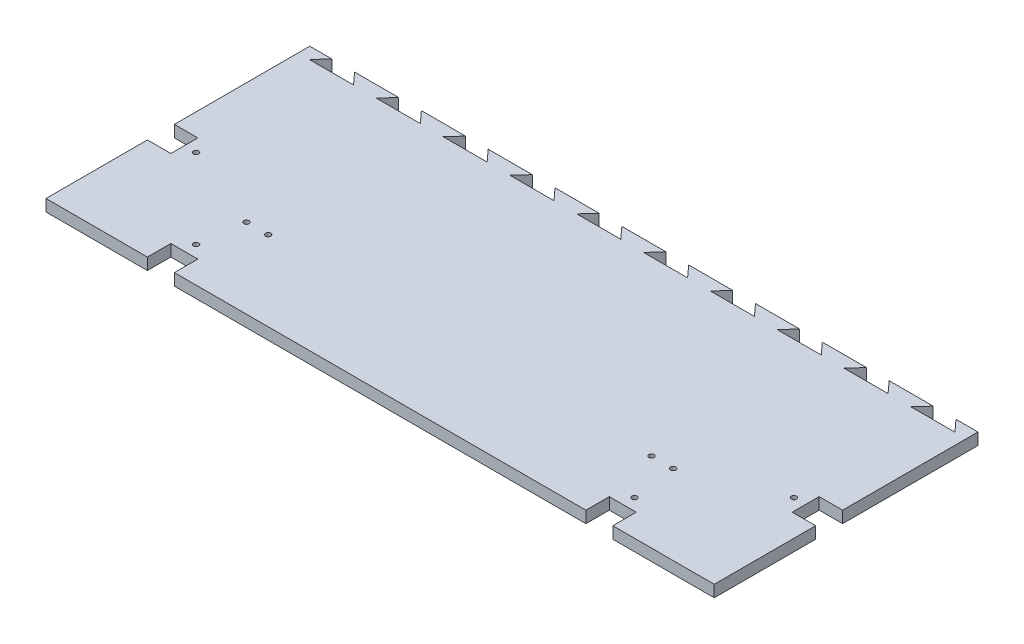
SolidWorks part; units mm, degrees
material "Multistrato di pioppo"
ref_plane "Piano frontale" through (0, 0, 0) normal (0, 0, 1) x (1, 0, 0)
ref_plane "Piano superiore" through (0, 0, 0) normal (0, 1, 0) x (1, 0, 0)
ref_plane "Piano destro" through (0, 0, 0) normal (1, 0, 0) x (0, 0, -1)
sketch "Schizzo1" plane through (0, 0, 0) normal (0, 1, 0) x (1, 0, 0)
  line L1 (0, 0) -> (-570, 0)
  line L2 (0, 0) -> (0, 450)
  line L3 (0, 450) -> (-570, 450)
  line L4 (-570, 0) -> (-570, 450)
  dimension "D1" = 570
  dimension "D2" = 450
extrude "Estrusione-Estrusione1" add sketch "Schizzo1" along normal blind 10
sketch "Schizzo2" plane through (0, 0, 0) normal (0, -1, 0) x (1, 0, 0)
  line L0 (-570, 0) -> (0, 0) construction
  line L1 (-483.5, 0) -> (-460.5, 0)
  line L3 (-483.5, 0) -> (-483.5, -20)
  line L5 (-483.5, -20) -> (-460.5, -20)
  line L6 (-460.5, 0) -> (-460.5, -20)
  line L7 (-483.5, 0) -> (-460.5, -20) construction
  line L8 (-483.5, -20) -> (-460.5, 0) construction
  line L9 (0, 0) -> (0, -450) construction
  line L10 (-109.5, 0) -> (-86.5, 0)
  line L11 (-109.5, 0) -> (-109.5, -20)
  line L12 (-109.5, -20) -> (-86.5, -20)
  line L13 (-86.5, 0) -> (-86.5, -20)
  line L14 (-109.5, 0) -> (-86.5, -20) construction
  line L15 (-109.5, -20) -> (-86.5, 0) construction
  line L16 (0, -86.5) -> (-20, -86.5)
  line L17 (0, -86.5) -> (0, -109.5)
  line L18 (0, -109.5) -> (-20, -109.5)
  line L19 (-20, -86.5) -> (-20, -109.5)
  line L20 (0, -86.5) -> (-20, -109.5) construction
  line L21 (0, -109.5) -> (-20, -86.5) construction
  line L22 (0, -450) -> (-570, -450) construction
  line L23 (0, -340.5) -> (-20, -340.5)
  line L24 (0, -340.5) -> (0, -363.5)
  line L25 (0, -363.5) -> (-20, -363.5)
  line L26 (-20, -340.5) -> (-20, -363.5)
  line L27 (0, -340.5) -> (-20, -363.5) construction
  line L28 (0, -363.5) -> (-20, -340.5) construction
  line L29 (-86.5, -450) -> (-109.5, -450)
  line L30 (-86.5, -450) -> (-86.5, -430)
  line L31 (-86.5, -430) -> (-109.5, -430)
  line L32 (-109.5, -450) -> (-109.5, -430)
  line L33 (-86.5, -450) -> (-109.5, -430) construction
  line L34 (-86.5, -430) -> (-109.5, -450) construction
  line L35 (-570, -450) -> (-570, 0) construction
  line L36 (-460.5, -450) -> (-483.5, -450)
  line L37 (-460.5, -450) -> (-460.5, -430)
  line L38 (-460.5, -430) -> (-483.5, -430)
  line L39 (-483.5, -450) -> (-483.5, -430)
  line L40 (-460.5, -450) -> (-483.5, -430) construction
  line L41 (-460.5, -430) -> (-483.5, -450) construction
  line L42 (-570, -363.5) -> (-550, -363.5)
  line L43 (-570, -363.5) -> (-570, -340.5)
  line L44 (-570, -340.5) -> (-550, -340.5)
  line L45 (-550, -363.5) -> (-550, -340.5)
  line L46 (-570, -363.5) -> (-550, -340.5) construction
  line L47 (-570, -340.5) -> (-550, -363.5) construction
  line L48 (-560, -98) -> (-10, -98) construction
  line L49 (-570, -109.5) -> (-550, -109.5)
  line L50 (-570, -109.5) -> (-570, -86.5)
  line L51 (-570, -86.5) -> (-550, -86.5)
  line L52 (-550, -109.5) -> (-550, -86.5)
  line L53 (-570, -109.5) -> (-550, -86.5) construction
  line L54 (-570, -86.5) -> (-550, -109.5) construction
  line L55 (-472, -10) -> (-472, -440) construction
  line L56 (-98, -440) -> (-98, -10) construction
  line L57 (-560, -352) -> (-10, -352) construction
  circle A2 centre (-467, -68) radius 2.25
  circle A3 centre (-448.5, -68) radius 2.25
  circle A6 centre (-121.5, -68) radius 2.25
  circle A7 centre (-103, -68) radius 2.25
  circle A8 centre (-467, -382) radius 2.25
  circle A9 centre (-448.5, -382) radius 2.25
  circle A14 centre (-121.5, -382) radius 2.25
  circle A15 centre (-103, -382) radius 2.25
  circle A16 centre (-472, -420) radius 2.25
  circle A17 centre (-540, -352) radius 2.25
  circle A18 centre (-540, -98) radius 2.25
  circle A19 centre (-472, -30) radius 2.25
  circle A20 centre (-98, -30) radius 2.25
  circle A21 centre (-30, -98) radius 2.25
  circle A22 centre (-30, -352) radius 2.25
  circle A23 centre (-98, -420) radius 2.25
  point P4 (-472, -10)
  point P17 (-98, -10)
  point P34 (-10, -98)
  point P41 (-10, -352)
  point P52 (-98, -440)
  point P59 (-472, -440)
  point P64 (-560, -352)
  point P71 (-560, -98)
  dimension "D1" = 4.5
  dimension "D3" = 98
  dimension "D5" = 98
  dimension "D2" = 98
  dimension "D4" = 98
  dimension "D6" = 23
  dimension "D7" = 20
extrude "Taglio-Estrusione1" cut sketch "Schizzo2" against normal blind 10
sketch "Schizzo3" plane through (0, 0, 0) normal (0, -1, 0) x (1, 0, 0)
  line L0 (-570, -225) -> (-551.2, -225)
  line L1 (-570, -340.5) -> (-570, -109.5) construction
  line L2 (-551.2, -225) -> (-560.3, -215)
  line L3 (-560.3, -215) -> (-522.7, -215)
  line L4 (-522.7, -215) -> (-531.8, -225)
  line L5 (-531.8, -225) -> (-513, -225)
  line L6 (-551.2, -225) -> (-531.8, -225) construction
  line L7 (-541.5, -225) -> (-541.5, -215) construction
  line L8 (-513, -225) -> (-494.2, -225)
  line L9 (-494.2, -225) -> (-503.3, -215)
  line L10 (-503.3, -215) -> (-465.7, -215)
  line L11 (-465.7, -215) -> (-474.8, -225)
  line L12 (-474.8, -225) -> (-456, -225)
  line L13 (-494.2, -225) -> (-474.8, -225) construction
  line L14 (-484.5, -225) -> (-484.5, -215) construction
  line L15 (-456, -225) -> (-437.2, -225)
  line L16 (-437.2, -225) -> (-446.3, -215)
  line L17 (-446.3, -215) -> (-408.7, -215)
  line L18 (-408.7, -215) -> (-417.8, -225)
  line L19 (-417.8, -225) -> (-399, -225)
  line L20 (-437.2, -225) -> (-417.8, -225) construction
  line L21 (-427.5, -225) -> (-427.5, -215) construction
  line L22 (-399, -225) -> (-380.2, -225)
  line L23 (-380.2, -225) -> (-389.3, -215)
  line L24 (-389.3, -215) -> (-351.7, -215)
  line L25 (-351.7, -215) -> (-360.8, -225)
  line L26 (-360.8, -225) -> (-342, -225)
  line L27 (-380.2, -225) -> (-360.8, -225) construction
  line L28 (-370.5, -225) -> (-370.5, -215) construction
  line L29 (-342, -225) -> (-323.2, -225)
  line L30 (-323.2, -225) -> (-332.3, -215)
  line L31 (-332.3, -215) -> (-294.7, -215)
  line L32 (-294.7, -215) -> (-303.8, -225)
  line L33 (-303.8, -225) -> (-285, -225)
  line L34 (-323.2, -225) -> (-303.8, -225) construction
  line L35 (-313.5, -225) -> (-313.5, -215) construction
  line L36 (-285, -225) -> (-266.2, -225)
  line L37 (-266.2, -225) -> (-275.3, -215)
  line L38 (-275.3, -215) -> (-237.7, -215)
  line L39 (-237.7, -215) -> (-246.8, -225)
  line L40 (-246.8, -225) -> (-228, -225)
  line L41 (-266.2, -225) -> (-246.8, -225) construction
  line L42 (-256.5, -225) -> (-256.5, -215) construction
  line L43 (-228, -225) -> (-209.2, -225)
  line L44 (-209.2, -225) -> (-218.3, -215)
  line L45 (-218.3, -215) -> (-180.7, -215)
  line L46 (-180.7, -215) -> (-189.8, -225)
  line L47 (-189.8, -225) -> (-171, -225)
  line L48 (-209.2, -225) -> (-189.8, -225) construction
  line L49 (-199.5, -225) -> (-199.5, -215) construction
  line L50 (-171, -225) -> (-152.2, -225)
  line L51 (-152.2, -225) -> (-161.3, -215)
  line L52 (-161.3, -215) -> (-123.7, -215)
  line L53 (-123.7, -215) -> (-132.8, -225)
  line L54 (-132.8, -225) -> (-114, -225)
  line L55 (-152.2, -225) -> (-132.8, -225) construction
  line L56 (-142.5, -225) -> (-142.5, -215) construction
  line L57 (-114, -225) -> (-95.2, -225)
  line L58 (-95.2, -225) -> (-104.3, -215)
  line L59 (-104.3, -215) -> (-66.7, -215)
  line L60 (-66.7, -215) -> (-75.8, -225)
  line L61 (-75.8, -225) -> (-57, -225)
  line L62 (-95.2, -225) -> (-75.8, -225) construction
  line L63 (-85.5, -225) -> (-85.5, -215) construction
  line L64 (-57, -225) -> (-38.2, -225)
  line L65 (-38.2, -225) -> (-47.3, -215)
  line L66 (-47.3, -215) -> (-9.7, -215)
  line L67 (-9.7, -215) -> (-18.8, -225)
  line L68 (-18.8, -225) -> (0, -225)
  line L69 (-38.2, -225) -> (-18.8, -225) construction
  line L70 (-28.5, -225) -> (-28.5, -215) construction
  line L71 (0, -109.5) -> (0, -340.5) construction
  line L72 (-570, -225) -> (-570, -450)
  line L73 (-570, -450) -> (0, -450)
  line L74 (0, -450) -> (0, -225)
  dimension "D1" = 57
  dimension "D2" = 10
  dimension "D3" = 37.6
  dimension "D4" = 19.4
  dimension "D5" = 10
extrude "Taglio-Estrusione2" cut sketch "Schizzo3" against normal blind 10
